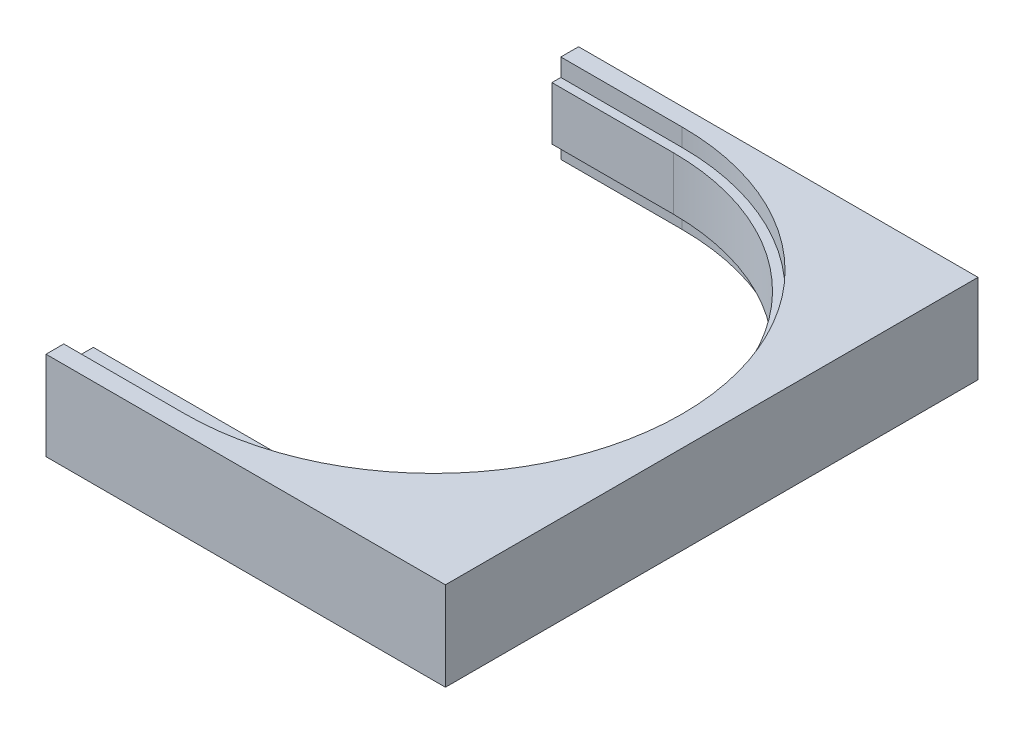
SolidWorks part; units mm, degrees
material "6061 Alloy"
ref_plane "Front Plane" through (0, 0, 0) normal (0, 0, 1) x (1, 0, 0)
ref_plane "Top Plane" through (0, 0, 0) normal (0, 1, 0) x (1, 0, 0)
ref_plane "Right Plane" through (0, 0, 0) normal (1, 0, 0) x (0, 0, -1)
sketch "Sketch1" plane through (0, 0, 0) normal (0, 1, 0) x (1, 0, 0)
  line L0 (0, 45.72) -> (0, 44.196)
  line L1 (0, 0) -> (34.29, 0)
  line L2 (0, 0) -> (0, 1.524)
  line L3 (0, 45.72) -> (34.29, 45.72)
  line L4 (34.29, 0) -> (34.29, 45.72)
  line L5 (0, 1.524) -> (10.414, 1.524)
  line L6 (0, 44.196) -> (10.414, 44.196)
  arc A0 (10.414, 44.196) -> (10.414, 1.524) centre (10.414, 22.86) cw
  dimension "D1" = 45.72
  dimension "D2" = 34.29
  dimension "D3" = 42.672
  dimension "D4" = 23.876
extrude "Boss-Extrude1" add sketch "Sketch1" along normal mid plane 7.62
sketch "Sketch2" plane through (0, 0, 0) normal (0, 1, 0) x (1, 0, 0)
  line L0 (0, 4.064) -> (18.7806, 4.064)
  line L1 (0, 43.434) -> (10.414, 43.434)
  line L2 (0, 1.524) -> (0, 0) construction
  line L3 (10.414, 1.524) -> (0, 1.524) construction
  line L4 (0, 44.196) -> (10.414, 44.196) construction
  line L5 (0, 43.434) -> (0, 44.196)
  line L6 (0, 44.196) -> (10.414, 44.196)
  line L7 (0, 4.064) -> (0, 1.524)
  line L8 (0, 1.524) -> (10.414, 1.524)
  arc A0 (10.414, 43.434) -> (18.7806, 4.064) centre (10.414, 22.86) cw
  arc A1 (10.414, 1.524) -> (10.414, 44.196) centre (10.414, 22.86) ccw construction
  arc A2 (10.414, 44.196) -> (10.414, 1.524) centre (10.414, 22.86) cw
  dimension "D1" = 0.762
  dimension "D2" = 2.54
  dimension "D3" = 0.762
extrude "Boss-Extrude2" add sketch "Sketch2" along normal mid plane 4.572
